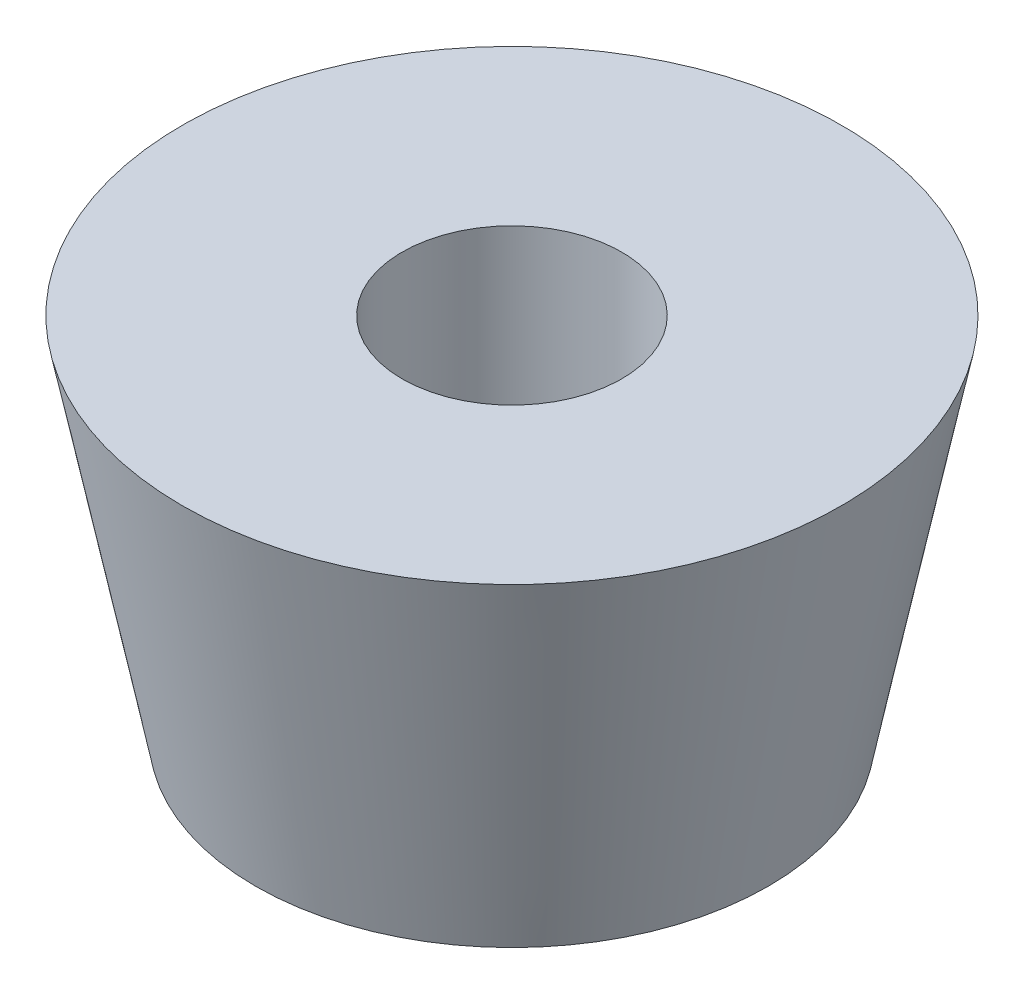
SolidWorks part; units mm, degrees
ref_plane "Front Plane" through (0, 0, 0) normal (0, 0, 1) x (1, 0, 0)
ref_plane "Top Plane" through (0, 0, 0) normal (0, 1, 0) x (1, 0, 0)
ref_plane "Right Plane" through (0, 0, 0) normal (1, 0, 0) x (0, 0, -1)
sketch "Sketch1" plane through (0, 0, 0) normal (1, 0, 0) x (0, 0, -1)
  line L0 (1.5, 0) -> (1.5, -5)
  line L1 (1.5, -5) -> (3.5, -5)
  line L2 (3.5, -5) -> (4.5, 0)
  line L3 (4.5, 0) -> (1.5, 0)
  line L4 (0, 0) -> (0, -5) construction
  point P7 (0, 0)
  dimension "D1" = 5
  dimension "D2" = 3
  dimension "D3" = 2
  dimension "D4" = 1.5
revolve "Revolve1" add sketch "Sketch1" angle 360 about L4
